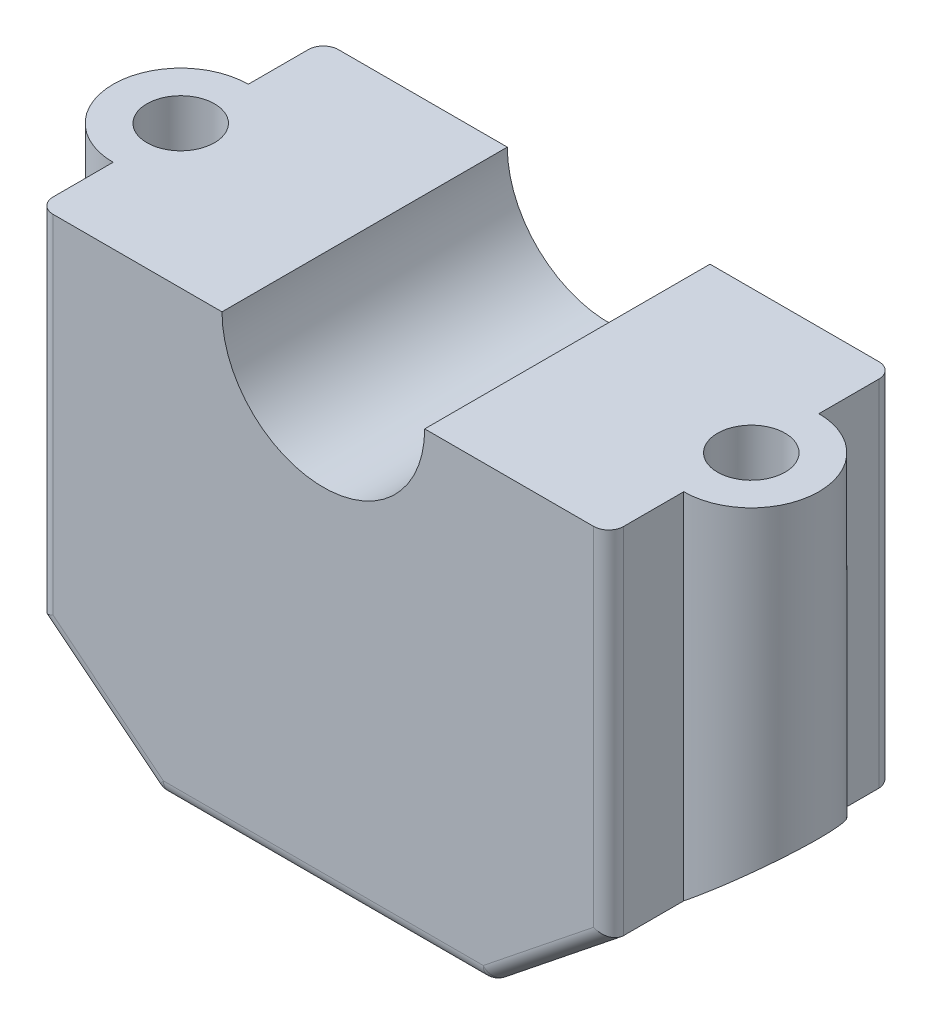
SolidWorks part; units mm, degrees
ref_plane "Plano frontal" through (0, 0, 0) normal (0, 0, 1) x (1, 0, 0)
ref_plane "Plano superior" through (0, 0, 0) normal (0, 1, 0) x (1, 0, 0)
ref_plane "Plano direito" through (0, 0, 0) normal (1, 0, 0) x (0, 0, -1)
sketch "Esboço2" plane through (0, 0, 0) normal (0, 1, 0) x (1, 0, 0)
  line L0 (-24.0936, 0) -> (24.0936, 0) construction
  line L1 (0, 17.9299) -> (0, -17.9299) construction
  line L3 (-38, 19) -> (38, 19)
  line L4 (-38, 19) -> (-38, -19)
  line L5 (-38, -19) -> (38, -19)
  line L6 (38, 19) -> (38, -19)
  line L7 (-38, 19) -> (38, -19) construction
  line L8 (-38, -19) -> (38, 19) construction
  circle A0 centre (-38, 0) radius 4.5
  circle A1 centre (-38, 0) radius 9
  circle A2 centre (38, 0) radius 4.5
  circle A3 centre (38, 0) radius 9
  point P4 (0, 0)
  point P6 (0, 0)
  point P8 (0, 0)
  dimension "D2" = 18
  dimension "D3" = 9
  dimension "D4" = 76
  dimension "D1" = 38
extrude "Ressalto-extrusão1" add sketch "Esboço2" along normal blind 60 contours A3 L6 L3 L4 A1 L5 | L4 A1 A0 | L4 A1 A0 | L6 A3 A2 | L6 A3 A2
sketch "Esboço3" plane through (0, 0, 19) normal (0, 0, 1) x (1, 0, 0)
  line L0 (0, 31.7801) -> (0, -31.7801) construction
  line L1 (-92.9646, 60) -> (92.9646, 60) construction
  line L2 (-38, 60) -> (38, 60) construction
  arc A0 (-13.5, 60) -> (13.5, 60) centre (0, 60) ccw
  arc A1 (-36, 60) -> (0, 96) centre (0, 60) ccw
  point P4 (0, 0)
  point P12 (0, 60)
  line M4 (38, 60) -> (-38, 60)
  dimension "D1" = 72
  dimension "D2" = 27
extrude "Corte-extrusão1" cut sketch "Esboço3" against normal through all contours A0 M4
sketch "Esboço4" plane through (0, 0, 0) normal (0, 0, 1) x (1, 0, 0)
  line L0 (-47, 20) -> (-22, 0)
  line L1 (-47, 60) -> (-47, 0) construction
  line L2 (-38, 0) -> (38, 0) construction
  line L3 (0, 82.9077) -> (0, -58.8327) construction
  dimension "D1" = 20
  dimension "D2" = 25
extrude "Corte-extrusão6" cut sketch "Esboço4" against normal through all both and the other way through all flip side to cut
sketch "Esboço5" plane through (0, 0, 0) normal (0, 0, 1) x (1, 0, 0)
  line L0 (47, 20) -> (22, 0)
  line L1 (47, 0) -> (47, 60) construction
  line L2 (-22, 0) -> (38, 0) construction
  dimension "D1" = 25
  dimension "D2" = 20
extrude "Corte-extrusão7" cut sketch "Esboço5" against normal through all both and the other way through all
fillet "Filete1" radius 2 12 edges at (22, 0, 0) (-38, 36.4, -19) (-30, 6.4, -19) (-22, 0, 0) (0, 0, -19) (30, 6.4, -19) (38, 36.4, -19) (30, 6.4, 19) (38, 36.4, 19) (-30, 6.4, 19) (-38, 36.4, 19) (0, 0, 19)
